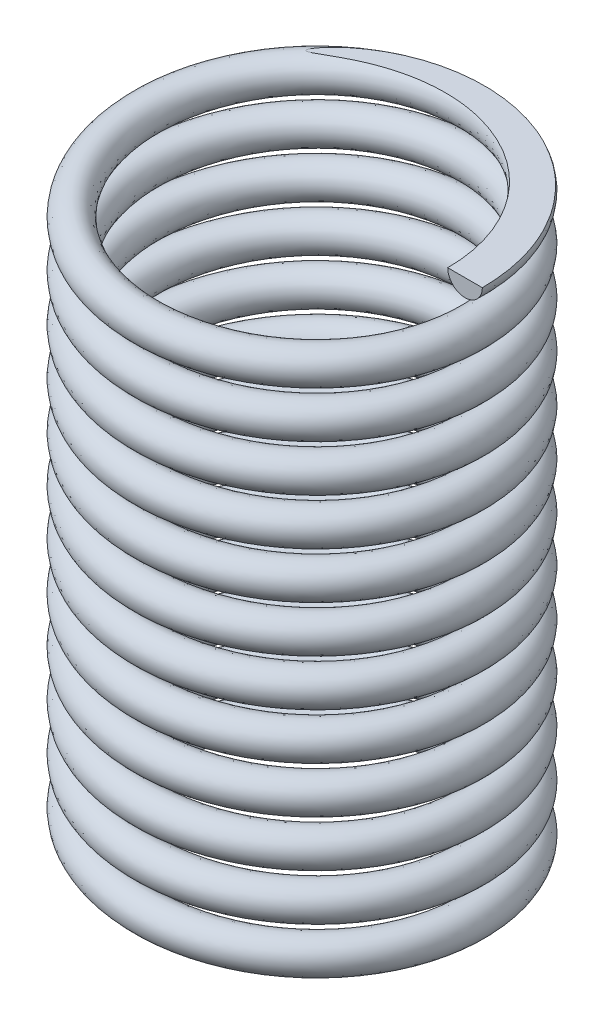
SolidWorks part; units mm, degrees
ref_plane "Front Plane" through (0, 0, 0) normal (0, 0, 1) x (1, 0, 0)
ref_plane "Top Plane" through (0, 0, 0) normal (0, 1, 0) x (1, 0, 0)
ref_plane "Right Plane" through (0, 0, 0) normal (1, 0, 0) x (0, 0, -1)
sketch "Sketch1" plane through (0, 0, 0) normal (0, 1, 0) x (1, 0, 0)
  circle A0 centre (0, 0) radius 66
curve "Helix/Spiral3" pitch 18.8 height 235 turns 12.5
sketch "Sketch3" plane through (0, 0, 0) normal (0, 0, 1) x (1, 0, 0)
  circle A0 centre (66, 235) radius 7
  point P2 (0, 0)
  point P3 (0, 0)
  point P6 (0, 0)
sweep "Sweep2" add profiles "Sketch3" path "Helix/Spiral3"
ref_plane "Plane2" through (0, 235, 0) normal (0, 1, 0) x (1, 0, 0)
other "SurfaceCut3"
ref_plane "Plane4" through (0, 0, 0) normal (0, 1, 0) x (1, 0, 0)
other "SurfaceCut4"
